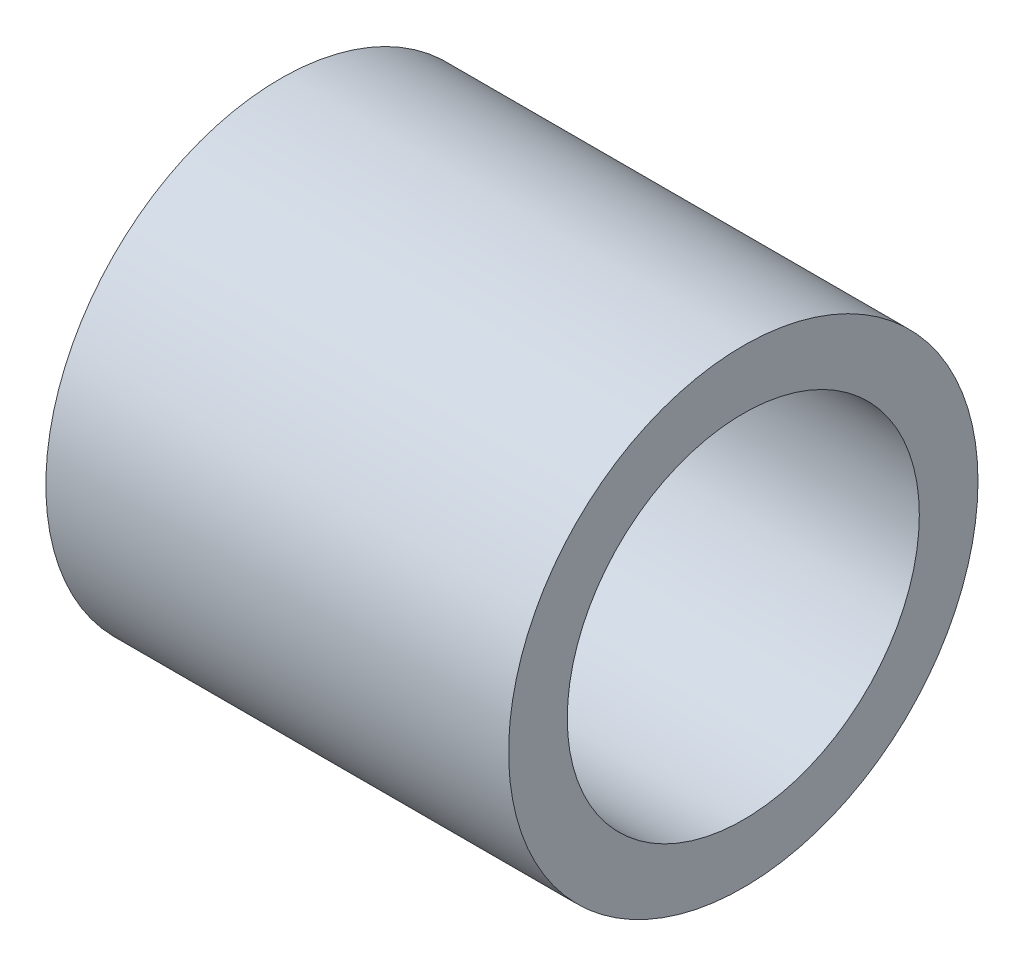
SolidWorks part; units mm, degrees
ref_plane "Front Plane" through (0, 0, 0) normal (0, 0, 1) x (1, 0, 0)
ref_plane "Top Plane" through (0, 0, 0) normal (0, 1, 0) x (1, 0, 0)
ref_plane "Right Plane" through (0, 0, 0) normal (1, 0, 0) x (0, 0, -1)
sketch "Sketch1" plane through (0, 0, 0) normal (1, 0, 0) x (0, 0, -1)
  circle A0 centre (0, 0) radius 9.525
  circle A1 centre (0, 0) radius 12.7
  dimension "D1" = 25.4
  dimension "D2" = 19.05
extrude "Boss-Extrude1" add sketch "Sketch1" along normal mid plane 25.04
